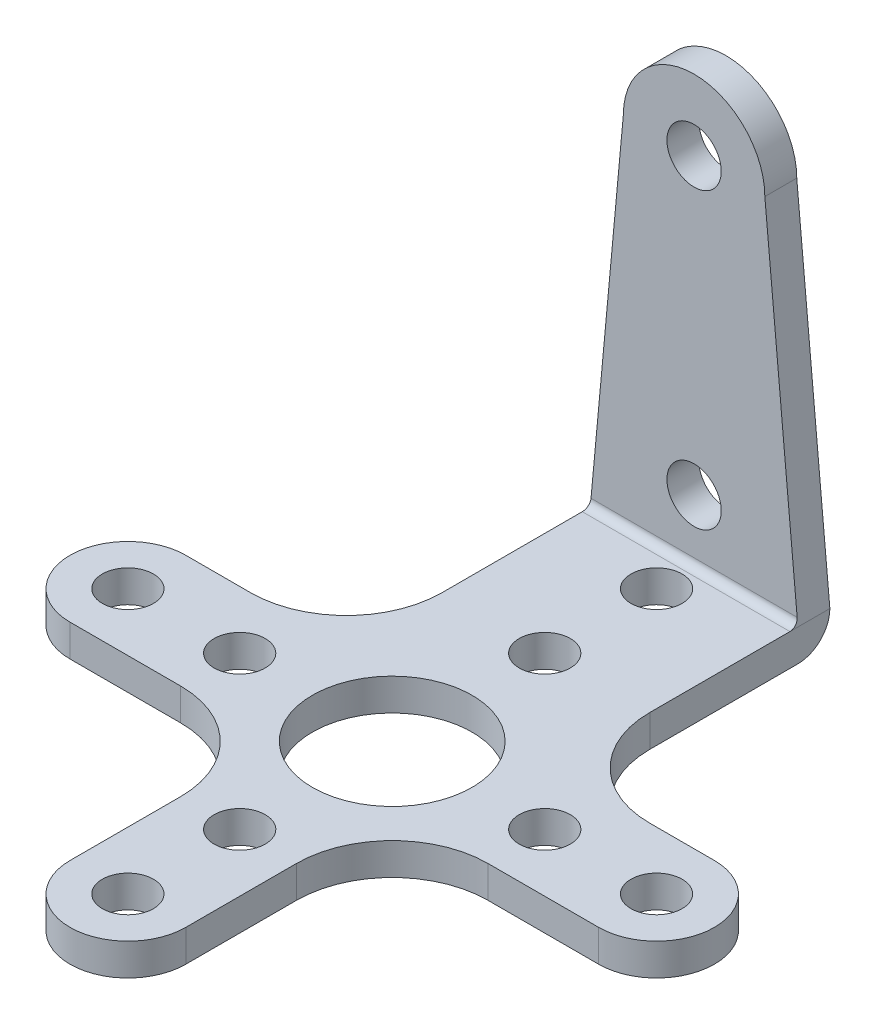
SolidWorks part; units mm, degrees
ref_plane "Plan de face" through (0, 0, 0) normal (0, 0, 1) x (1, 0, 0)
ref_plane "Plan de dessus" through (0, 0, 0) normal (0, 1, 0) x (1, 0, 0)
ref_plane "Plan de droite" through (0, 0, 0) normal (1, 0, 0) x (0, 0, -1)
sketch "Esquisse1" plane through (0, 0, 0) normal (0, 1, 0) x (1, 0, 0)
  line L0 (0, 0) -> (-20.1, 0) construction
  line L1 (0, 0) -> (20.1, 0) construction
  line L2 (-23.8503, 3.625) -> (23.8503, 3.625) construction
  line L3 (-23.8503, -3.625) -> (24.4927, -3.625) construction
  line L4 (0, 3.625) -> (0, -3.625) construction
  line L5 (-16.55, -3.625) -> (-16.55, 3.625) construction
  line L6 (0, 3.625) -> (0, 11.6567) construction
  line L7 (0, -3.625) -> (0, -20.1) construction
  line L8 (-16.55, 3.625) -> (-12.5, 3.625)
  line L9 (-16.55, -3.625) -> (-9.625, -3.625)
  line L10 (16.55, -3.625) -> (9.625, -3.625)
  line L11 (16.55, 3.625) -> (12.5, 3.625)
  line L12 (0, 0) -> (-10.0245, -10.0245) construction
  line L13 (-3.625, -16.55) -> (-3.625, -9.625)
  line L14 (3.625, -16.55) -> (3.625, -9.625)
  line L15 (-3.625, -3.625) -> (-3.625, -2.6439) construction
  line L16 (-6.5, 3.625) -> (-6.5, 17.4349) construction
  line L17 (6.5, 3.625) -> (6.5, 18.9) construction
  line L18 (-6.5, 9.8741) -> (6.5, 9.8741) construction
  line L19 (-6.5, 9.625) -> (-6.5, 18.9)
  line L20 (6.5, 9.625) -> (6.5, 18.9)
  line L21 (-6.5, 18.9) -> (6.5, 18.9)
  circle A0 centre (0, 0) radius 5
  circle A1 centre (-9.55, 0) radius 1.6
  circle A2 centre (-16.55, 0) radius 1.6
  circle A3 centre (9.55, 0) radius 1.6
  circle A4 centre (16.55, 0) radius 1.6
  arc A5 (-16.55, -3.625) -> (-16.55, 3.625) centre (-16.55, 0) cw
  arc A7 (16.55, -3.625) -> (16.55, 3.625) centre (16.55, 0) ccw
  circle A8 centre (0, -9.55) radius 1.6
  circle A9 centre (0, -16.55) radius 1.6
  arc A10 (-3.625, -16.55) -> (3.625, -16.55) centre (0, -16.55) ccw
  arc A12 (-3.625, -9.625) -> (-9.625, -3.625) centre (-9.625, -9.625) ccw
  arc A13 (9.625, -3.625) -> (3.625, -9.625) centre (9.625, -9.625) ccw
  arc A15 (-6.5, 9.625) -> (-12.5, 3.625) centre (-12.5, 9.625) cw
  arc A16 (12.5, 3.625) -> (6.5, 9.625) centre (12.5, 9.625) cw
  circle A17 centre (0, 16.55) radius 1.6
  circle A18 centre (0, 9.55) radius 1.6
  point P11 (0, 0)
  point P12 (5, 0)
  point P13 (-5, 0)
  point P14 (-11.15, 0)
  point P15 (-11.15, 0)
  point P16 (-9.55, 0)
  point P19 (-7.95, 0)
  point P20 (-18.15, 0)
  point P21 (-16.55, 0)
  point P54 (3.625, -3.625)
  point P58 (0, 9.8741)
  dimension "D1" = 10
  dimension "D9" = 6
  dimension "D12" = 6
  dimension "D17" = 6
  dimension "D18" = 6
  dimension "D2" = 20.1
  dimension "D3" = 20.1
  dimension "D4" = 7.25
  dimension "D5" = 16.15
  dimension "D6" = 1.6
  dimension "D7" = 10.2
  dimension "D8" = 1.6
  dimension "D10" = 20.1
  dimension "D11" = 45
  dimension "D13" = 13
  dimension "D15" = 39
  dimension "D16" = 39
extrude "Boss.-Extru.1" add sketch "Esquisse1" along normal blind 2
ref_plane "Plan1" through (0, 0, -18.9) normal (0, 0, -1) x (-1, 0, 0)
sketch "Esquisse2" plane through (0, 0, -18.9) normal (0, 0, -1) x (-1, 0, 0)
  line L0 (-6.5, 0) -> (6.5, 0)
  line L1 (6.5, 0) -> (6.5, 2)
  line L2 (-6.5, 0) -> (-6.5, 2)
  line L3 (0, 2) -> (0, 72) construction
  line L4 (-6.5, 2) -> (6.5, 2) construction
  line L5 (0, 72) -> (6.5, 2) construction
  line L6 (0, 72) -> (-6.5, 2) construction
  line L7 (0, 24.3) -> (-4.4293, 24.3) construction
  line L8 (-4.4293, 24.3) -> (4.4293, 24.3) construction
  line L9 (-6.5, 2) -> (-4.4293, 24.3)
  line L10 (4.4293, 24.3) -> (6.5, 2)
  circle A0 centre (0, 24.3) radius 1.7
  circle A1 centre (0, 5.9) radius 1.7
  arc A2 (4.4293, 24.3) -> (-4.4293, 24.3) centre (0, 24.3) ccw
  point P13 (0, 28)
  point P14 (0, 26)
  point P15 (0, 24.3)
  point P18 (0, 4.2)
  point P19 (0, 22.6)
  point P20 (0, 5.9)
  dimension "D1" = 26
  dimension "D2" = 70
  dimension "D3" = 2
  dimension "D4" = 1.7
  dimension "D5" = 18.4
  dimension "D6" = 1.7
extrude "Boss.-Extru.2" add sketch "Esquisse2" along normal blind 2
fillet "Congé2" radius 2 1 edges at (0, 0, -20.9)
fillet "Congé3" radius 0.5 1 edges at (0, 2, -18.9)
